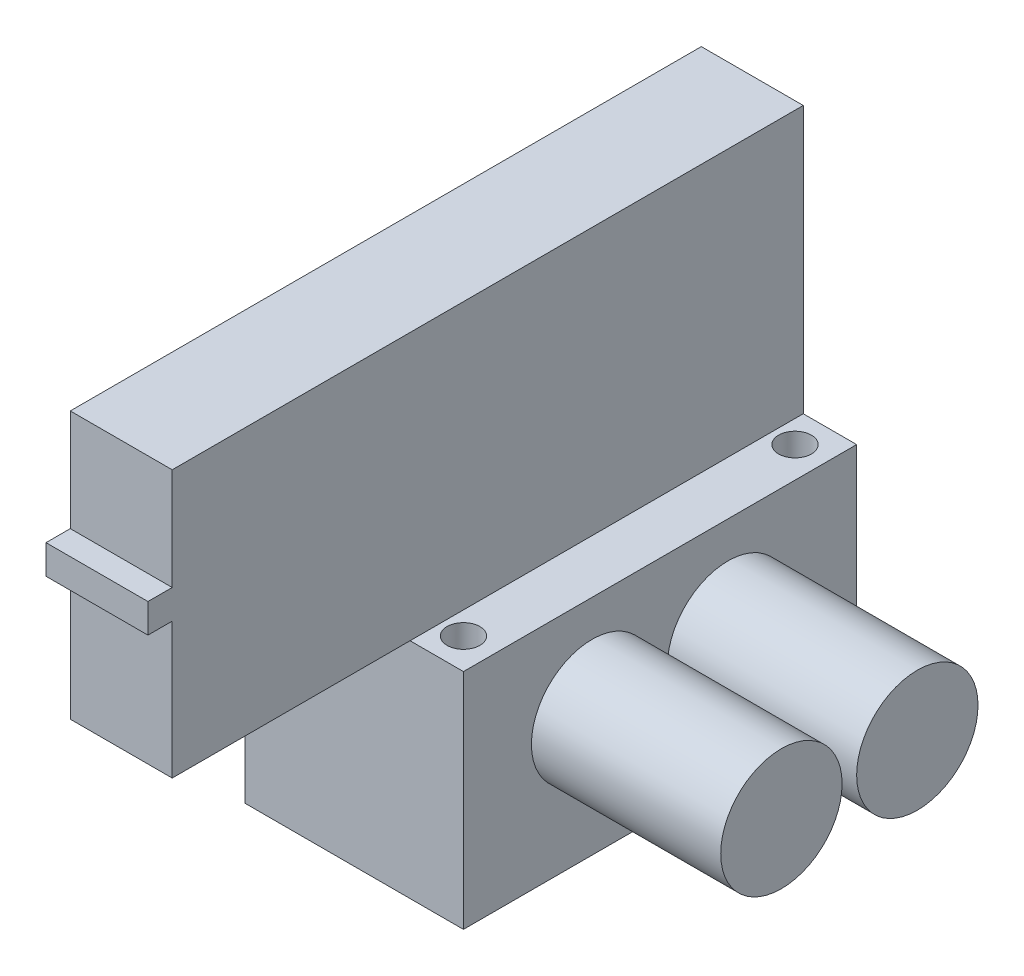
SolidWorks part; units mm, degrees
ref_plane "Front Plane" through (0, 0, 0) normal (0, 0, 1) x (1, 0, 0)
ref_plane "Top Plane" through (0, 0, 0) normal (0, 1, 0) x (1, 0, 0)
ref_plane "Right Plane" through (0, 0, 0) normal (1, 0, 0) x (0, 0, -1)
sketch "Sketch1" plane through (0, 0, 0) normal (0, 1, 0) x (1, 0, 0)
  line L1 (0, 0) -> (22.86, 0)
  line L2 (0, 0) -> (0, 41.148)
  line L3 (0, 41.148) -> (22.86, 41.148)
  line L4 (22.86, 0) -> (22.86, 41.148)
  dimension "D1" = 41.148
  dimension "D2" = 22.86
extrude "Boss-Extrude1" add sketch "Sketch1" along normal blind 23.368
sketch "Sketch2" plane through (0, 23.368, 0) normal (0, 1, 0) x (1, 0, 0)
  line L0 (22.86, 41.148) -> (0, 41.148) construction
  line L1 (6.604, 41.148) -> (17.272, 41.148)
  line L2 (6.604, 41.148) -> (6.604, -24.892)
  line L3 (6.604, -24.892) -> (17.272, -24.892)
  line L4 (17.272, 41.148) -> (17.272, -24.892)
  line L5 (0, 41.148) -> (0, 0) construction
  dimension "D1" = 6.604
  dimension "D2" = 10.668
  dimension "D3" = 66.04
extrude "Boss-Extrude2" add sketch "Sketch2" along normal blind 27.94
sketch "Sketch3" plane through (0, 0, 0) normal (-1, 0, 0) x (0, 0, 1)
  line L0 (-41.148, 23.368) -> (0, 23.368) construction
  line L1 (-41.148, 23.368) -> (-41.148, 0) construction
  circle A0 centre (-20.828, 16.256) radius 6.35
  dimension "D1" = 12.7
  dimension "D2" = 7.112
  dimension "D3" = 20.32
extrude "Boss-Extrude3" add sketch "Sketch3" along normal blind 19.812
sketch "Sketch4" plane through (22.86, 0, 0) normal (1, 0, 0) x (0, 0, -1)
  line L0 (0, 23.368) -> (41.148, 23.368) construction
  line L1 (41.148, 23.368) -> (41.148, 0) construction
  line L2 (0, 23.368) -> (0, 0) construction
  circle A0 centre (27.686, 13.208) radius 6.35
  circle A1 centre (13.462, 13.208) radius 6.35
  dimension "D1" = 12.7
  dimension "D2" = 12.7
  dimension "D3" = 10.16
  dimension "D4" = 10.16
  dimension "D5" = 13.462
  dimension "D6" = 13.462
extrude "Boss-Extrude4" add sketch "Sketch4" along normal blind 19.812
sketch "Sketch5" plane through (0, 0, 24.892) normal (0, 0, 1) x (1, 0, 0)
  line L0 (6.604, 51.308) -> (6.604, 23.368) construction
  line L1 (6.604, 40.64) -> (17.272, 40.64)
  line L2 (6.604, 40.64) -> (6.604, 37.592)
  line L3 (6.604, 37.592) -> (17.272, 37.592)
  line L4 (17.272, 40.64) -> (17.272, 37.592)
  line L5 (17.272, 51.308) -> (17.272, 23.368) construction
  line L6 (6.604, 51.308) -> (17.272, 51.308) construction
  dimension "D1" = 13.716
  dimension "D2" = 3.048
extrude "Boss-Extrude5" add sketch "Sketch5" along normal blind 2.54
sketch "Sketch6" plane through (0, 0, 0) normal (0, -1, 0) x (-1, 0, 0)
  line L0 (-22.86, 0) -> (-22.86, 41.148) construction
  line L1 (-22.86, 41.148) -> (0, 41.148) construction
  line L2 (0, 0) -> (-22.86, 0) construction
  circle A0 centre (-19.6342, 3.2258) radius 1.7145
  circle A1 centre (-19.6342, 37.9222) radius 1.7145
  dimension "D1" = 3.429
  dimension "D2" = 3.429
  dimension "D3" = 3.2258
  dimension "D4" = 3.2258
  dimension "D5" = 3.2258
  dimension "D6" = 3.2258
extrude "Cut-Extrude1" cut sketch "Sketch6" against normal through all
